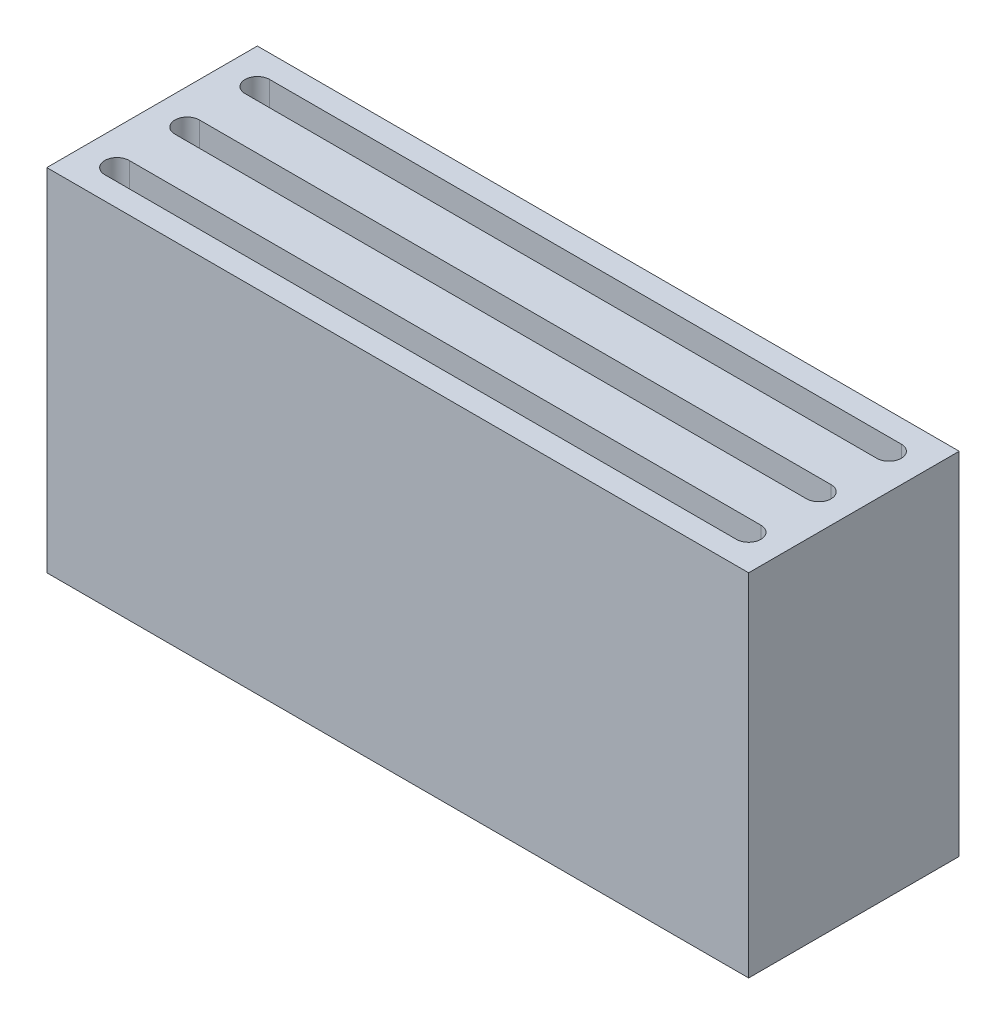
SolidWorks part; units mm, degrees
ref_plane "前视基准面" through (0, 0, 0) normal (0, 0, 1) x (1, 0, 0)
ref_plane "上视基准面" through (0, 0, 0) normal (0, 1, 0) x (1, 0, 0)
ref_plane "右视基准面" through (0, 0, 0) normal (1, 0, 0) x (0, 0, -1)
other "Configuration Table"
sketch "草图1" plane through (0, 0, 0) normal (0, 1, 0) x (1, 0, 0)
  line L1 (0, 0) -> (100, 0)
  line L2 (0, 0) -> (0, 30)
  line L3 (0, 30) -> (100, 30)
  line L4 (100, 0) -> (100, 30)
  dimension "D1" = 30
  dimension "D2" = 100
extrude "凸台-拉伸1" add sketch "草图1" along normal blind 50
sketch "草图2" plane through (0, 50, 0) normal (0, 1, 0) x (1, 0, 0)
  line L0 (0, 0) -> (0, 5) construction
  line L1 (0, 30) -> (0, 0) construction
  line L2 (0, 5) -> (5, 5) construction
  line L3 (100, 5) -> (95, 5) construction
  line L4 (100, 0) -> (100, 30) construction
  line L5 (5, 5) -> (95, 5) construction
  line L6 (5, 6.75) -> (95, 6.75)
  line L7 (5, 3.25) -> (95, 3.25)
  arc A0 (5, 6.75) -> (5, 3.25) centre (5, 5) ccw
  arc A1 (95, 3.25) -> (95, 6.75) centre (95, 5) ccw
  point P10 (50, 5)
  dimension "D1" = 5
  dimension "D2" = 5
  dimension "D3" = 5
extrude "切除-拉伸1" cut sketch "草图2" against normal blind 50
pattern_linear "阵列(线性)1" count 3 spacing 10 along (0, 0, -1) of "切除-拉伸1"
